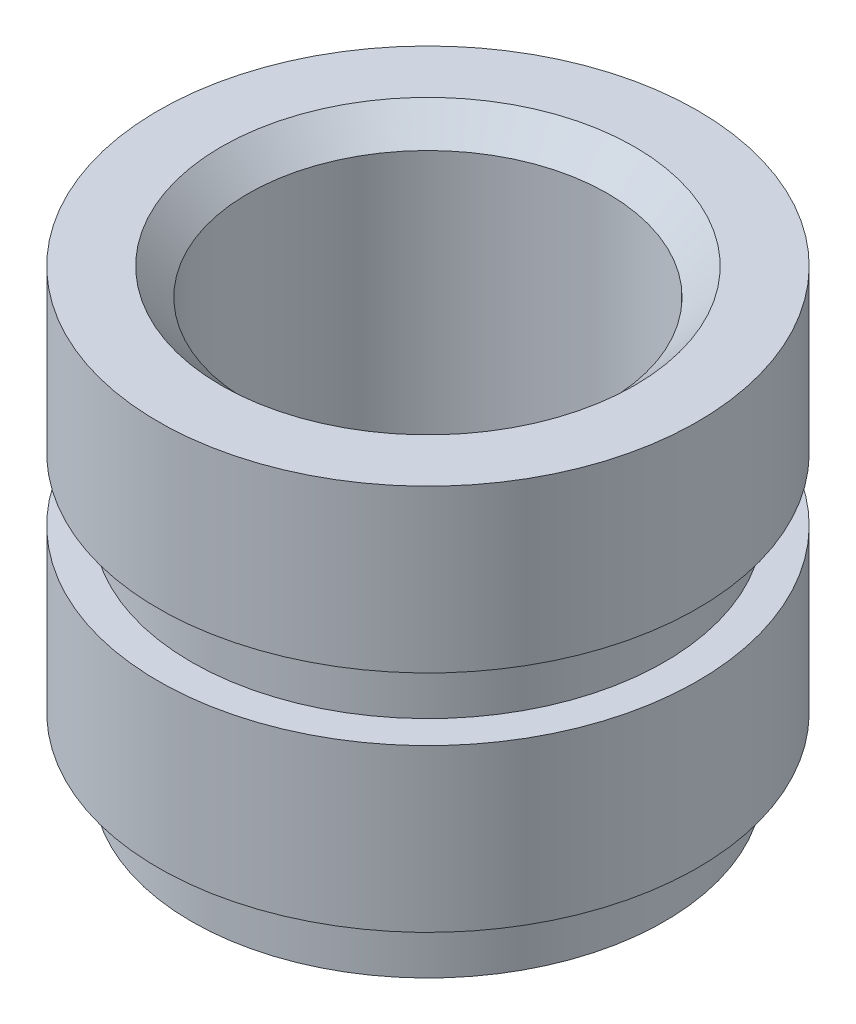
SolidWorks part; units mm, degrees
ref_plane "前视基准面" through (0, 0, 0) normal (0, 0, 1) x (1, 0, 0)
ref_plane "上视基准面" through (0, 0, 0) normal (0, 1, 0) x (1, 0, 0)
ref_plane "右视基准面" through (0, 0, 0) normal (1, 0, 0) x (0, 0, -1)
sketch "草图1" plane through (0, 0, 0) normal (0, 0, 1) x (1, 0, 0)
  line L0 (0, -2.6047) -> (0, 3.6552) construction
  line L1 (-1, 1.4338) -> (-1.5, 1.4338)
  line L2 (-1.5, 1.4338) -> (-1.5, 0.5338)
  line L3 (-1.5, 0.5338) -> (-1.3159, 0.5338)
  line L4 (-1.3159, 0.5338) -> (-1.3159, 0.1838)
  line L5 (-1, -1.0662) -> (-1.3159, -1.0662)
  line L10 (-1, -1.0662) -> (-1, 1.4338)
  line L11 (-1.3159, 0.1838) -> (-1.5, 0.1838)
  line L12 (-1.5, 0.1838) -> (-1.5, -0.7162)
  line L13 (-1.5, -0.7162) -> (-1.3159, -0.7162)
  line L14 (-1.3159, -0.7162) -> (-1.3159, -1.0662)
  dimension "D1" = 1.5
  dimension "D2" = 2.5
  dimension "D3" = 0.9
  dimension "D4" = 1
revolve "旋转1" add sketch "草图1" angle 360 about L0
chamfer "倒角1" distance 0.15 angle 45 2 edges at (0, 1.4338, -1) (0, -1.0662, -1)
